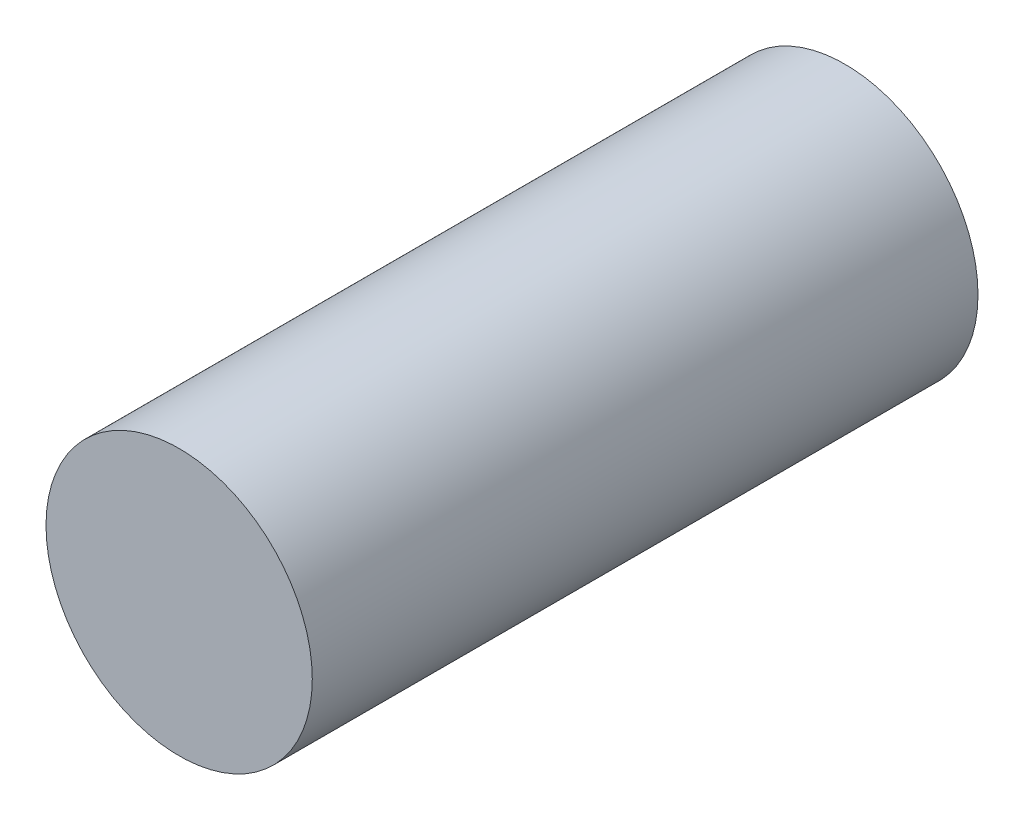
SolidWorks part; units mm, degrees
ref_plane "Front" through (0, 0, 0) normal (0, 0, 1) x (1, 0, 0)
ref_plane "Top" through (0, 0, 0) normal (0, 1, 0) x (1, 0, 0)
ref_plane "Right" through (0, 0, 0) normal (1, 0, 0) x (0, 0, -1)
sketch "Sketch1" plane through (0, 0, 0) normal (0, 0, 1) x (1, 0, 0)
  circle A0 centre (-16.3593, 0) radius 4
extrude "Boss-Extrude1" add sketch "Sketch1" along normal blind 20
